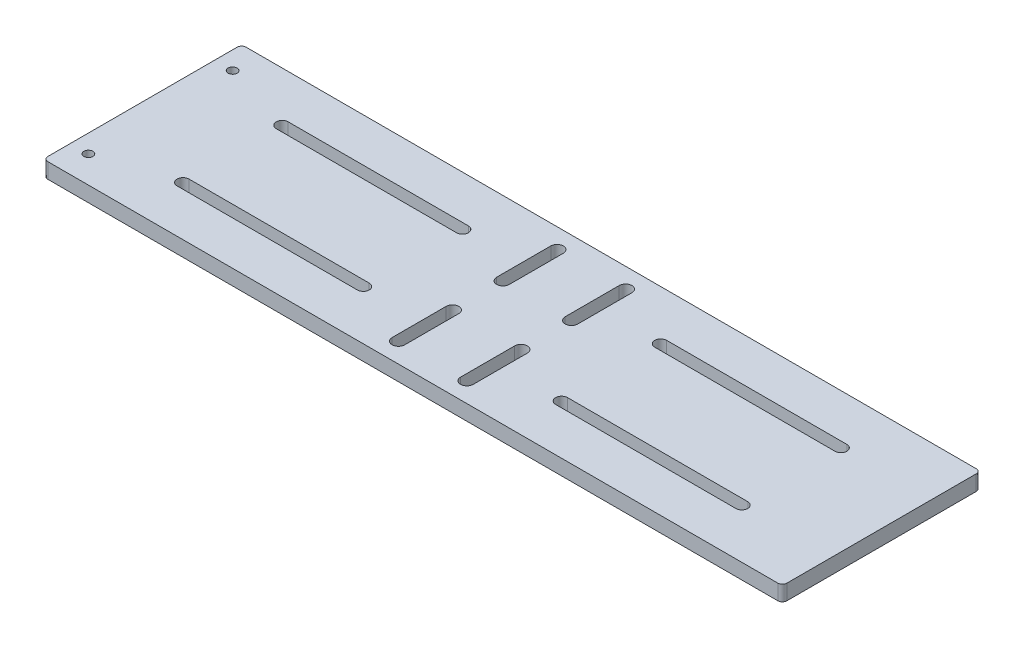
SolidWorks part; units mm, degrees
ref_plane "Front Plane" through (0, 0, 0) normal (0, 0, 1) x (1, 0, 0)
ref_plane "Top Plane" through (0, 0, 0) normal (0, 1, 0) x (1, 0, 0)
ref_plane "Right Plane" through (0, 0, 0) normal (1, 0, 0) x (0, 0, -1)
sketch "Sketch1" plane through (0, 0, 0) normal (0, 1, 0) x (1, 0, 0)
  line L1 (-19, 34) -> (19, 34) construction
  line L2 (-19, 34) -> (-19, -34) construction
  line L3 (-19, -34) -> (19, -34) construction
  line L4 (19, 34) -> (19, -34) construction
  line L5 (0, -34) -> (0, 34) construction
  line L6 (-19, 0) -> (19, 0) construction
  line L7 (-200, 50) -> (200, 50) construction
  line L8 (-200, 50) -> (-200, -50) construction
  line L9 (-200, -50) -> (200, -50) construction
  line L10 (200, 50) -> (200, -50) construction
  line L11 (0, -50) -> (0, 50) construction
  line L12 (-200, 0) -> (200, 0) construction
  line L13 (-205, 55) -> (205, 55)
  line L14 (-205, 55) -> (-205, -55)
  line L15 (-205, -55) -> (205, -55)
  line L16 (205, 55) -> (205, -55)
  line L17 (0, -55) -> (0, 55) construction
  line L18 (-205, 0) -> (205, 0) construction
  point P0 (0, 0)
  point P4 (0, 0)
  point P8 (0, 0)
  point P14 (-190, 40)
  point P16 (-190, -40)
  dimension "D2" = 68
  dimension "D3" = 400
  dimension "D4" = 100
  dimension "D5" = 5
  dimension "D6" = 5
  dimension "D10" = 10
  dimension "D11" = 10
  dimension "D12" = 10
  dimension "D13" = 38
extrude "Boss-Extrude1" add sketch "Sketch1" along normal blind 8.5
sketch "Sketch2" plane through (0, 8.5, 0) normal (0, 1, 0) x (1, 0, 0)
  line L0 (-205, 55) -> (-205, -55) construction
  line L1 (205, 55) -> (-205, 55) construction
  line L2 (-205, -55) -> (205, -55) construction
  point P0 (-195, -40)
  point P2 (-195, 40)
  dimension "D1" = 10
  dimension "D3" = 10
  dimension "D2" = 15
  dimension "D4" = 15
sketch "Sketch3" plane through (0, 8.5, 0) normal (0, 1, 0) x (1, 0, 0)
  point P8 (19, 34)
  point P10 (19, -34)
  point P12 (-19, -34)
  point P14 (-19, 34)
hole_wizard "M4 Clearance Hole1" positions "Sketch2" profile "Sketch4" hole size "M4" standard "ISO" end condition through all
sketch "Sketch4" plane through (-195, 8.5, 40) normal (1, 0, 0) x (0, 0, 1)
  line L0 (0, 0) -> (0, 8.5)
  line L1 (0, 8.5) -> (2.5, 8.5)
  line L2 (2.5, 8.5) -> (2.5, 0)
  line L5 (2.5, 0) -> (0, 0)
  line L11 (0, -6.35) -> (0, 107.95) construction
  dimension "Thru Hole Dia." = 5
  dimension "Thru Hole Depth" = 8.5
hole_wizard "M6 Clearance Hole1" positions "Sketch3" profile "Sketch5" hole size "M6" standard "ISO" end condition through all
sketch "Sketch5" plane through (19, 8.5, -34) normal (1, 0, 0) x (0, 0, 1)
  line L0 (0, 0) -> (0, 8.5)
  line L1 (0, 8.5) -> (3.5, 8.5)
  line L2 (3.5, 8.5) -> (3.5, 0)
  line L5 (3.5, 0) -> (0, 0)
  line L11 (0, -6.35) -> (0, 107.95) construction
  dimension "Thru Hole Dia." = 7
  dimension "Thru Hole Depth" = 8.5
fillet "Fillet1" radius 2.5 4 edges at (205, 4.25, -55) (205, 4.25, 55) (-205, 4.25, 55) (-205, 4.25, -55)
sketch "Sketch6" plane through (0, 8.5, 0) normal (0, 1, 0) x (1, 0, 0)
  line L0 (-22.5, 34) -> (-22.5, 14)
  line L1 (-15.5, 34) -> (-15.5, 14)
  line L2 (-19, 34) -> (19, 34) construction
  line L3 (-19, -34) -> (19, -34) construction
  line L4 (22.5, 34) -> (22.5, 14)
  line L5 (15.5, 34) -> (15.5, 14)
  line L6 (-22.5, 34) -> (-22.5, 44)
  line L7 (-15.5, 34) -> (-15.5, 44)
  line L8 (15.5, 34) -> (15.5, 44)
  line L9 (22.5, 34) -> (22.5, 44)
  line L10 (-22.5, -44) -> (-22.5, -34)
  line L11 (-15.5, -44) -> (-15.5, -34)
  line L12 (15.5, -44) -> (15.5, -34)
  line L13 (22.5, -44) -> (22.5, -34)
  line L14 (-22.5, 14) -> (-22.5, -14) construction
  line L15 (-22.5, -14) -> (-22.5, -34)
  line L16 (-15.5, 14) -> (-15.5, -14) construction
  line L17 (-15.5, -14) -> (-15.5, -34)
  line L18 (15.5, 14) -> (15.5, -14) construction
  line L19 (15.5, -14) -> (15.5, -34)
  line L20 (22.5, 14) -> (22.5, -14) construction
  line L21 (22.5, -14) -> (22.5, -34)
  circle A0 centre (-19, 34) radius 3.5 construction
  circle A1 centre (-19, -34) radius 3.5 construction
  circle A2 centre (19, 34) radius 3.5 construction
  circle A3 centre (19, -34) radius 3.5 construction
  arc A4 (-15.5, 34) -> (-22.5, 34) centre (-19, 34) ccw construction
  arc A5 (22.5, 34) -> (15.5, 34) centre (19, 34) ccw construction
  arc A6 (-22.5, -34) -> (-15.5, -34) centre (-19, -34) ccw construction
  arc A7 (15.5, -34) -> (22.5, -34) centre (19, -34) ccw construction
  arc A8 (-22.5, 34) -> (-15.5, 34) centre (-19, 34) ccw construction
  arc A9 (-15.5, -34) -> (-22.5, -34) centre (-19, -34) ccw construction
  arc A10 (22.5, -34) -> (15.5, -34) centre (19, -34) ccw construction
  arc A11 (15.5, 34) -> (22.5, 34) centre (19, 34) ccw construction
  arc A12 (-15.5, 44) -> (-22.5, 44) centre (-19, 44) ccw
  arc A13 (22.5, 44) -> (15.5, 44) centre (19, 44) ccw
  arc A14 (-22.5, -44) -> (-15.5, -44) centre (-19, -44) ccw
  arc A15 (15.5, -44) -> (22.5, -44) centre (19, -44) ccw
  arc A16 (22.5, -44) -> (15.5, -44) centre (19, -44) ccw construction
  arc A17 (-15.5, -44) -> (-22.5, -44) centre (-19, -44) ccw construction
  arc A18 (-22.5, 44) -> (-15.5, 44) centre (-19, 44) ccw construction
  arc A19 (15.5, 44) -> (22.5, 44) centre (19, 44) ccw construction
  arc A20 (-15.5, -14) -> (-22.5, -14) centre (-19, -14) ccw
  arc A21 (-22.5, 14) -> (-15.5, 14) centre (-19, 14) ccw
  arc A22 (15.5, 14) -> (22.5, 14) centre (19, 14) ccw
  arc A23 (22.5, -14) -> (15.5, -14) centre (19, -14) ccw
  arc A24 (-15.5, 14) -> (-22.5, 14) centre (-19, 14) ccw construction
  arc A25 (22.5, 14) -> (15.5, 14) centre (19, 14) ccw construction
  arc A26 (15.5, -14) -> (22.5, -14) centre (19, -14) ccw construction
  arc A27 (-22.5, -14) -> (-15.5, -14) centre (-19, -14) ccw construction
  dimension "D6" = 7
  dimension "D8" = 7
  dimension "D11" = 7
  dimension "D12" = 7
  dimension "D1" = 10
  dimension "D2" = 10
  dimension "D3" = 10
  dimension "D4" = 10
  dimension "D5" = 20
  dimension "D7" = 20
  dimension "D9" = 20
  dimension "D10" = 20
extrude "Cut-Extrude1" cut sketch "Sketch6" against normal up to surface (8.5 mm away) up to face at (19, 0, -30.5)
sketch "Sketch7" plane through (0, 8.5, 0) normal (0, 1, 0) x (1, 0, 0)
  line L0 (-205, 0) -> (205, 0) construction
  line L1 (-205, 52.5) -> (-205, -52.5) construction
  line L2 (205, -52.5) -> (205, 52.5) construction
  line L3 (-205, 27.5) -> (-158.3, 27.5) construction
  line L4 (-205, -27.5) -> (-158.3, -27.5) construction
  line L5 (202.5, 55) -> (-202.5, 55) construction
  line L6 (-155, 30.8) -> (-55, 30.8)
  line L7 (-155, 24.2) -> (-55, 24.2)
  line L8 (-155, -24.2) -> (-55, -24.2)
  line L9 (-55, -30.8) -> (-155, -30.8)
  line L10 (-158.3, -27.5) -> (-151.7, -27.5) construction
  line L11 (-151.7, -27.5) -> (-58.3, -27.5) construction
  line L12 (-58.3, -27.5) -> (-51.7, -27.5) construction
  line L13 (-51.7, -27.5) -> (51.7, -27.5) construction
  line L14 (-158.3, 27.5) -> (-151.7, 27.5) construction
  line L15 (-151.7, 27.5) -> (-58.3, 27.5) construction
  line L16 (-58.3, 27.5) -> (-51.7, 27.5) construction
  line L17 (-51.7, 27.5) -> (51.7, 27.5) construction
  line L18 (55, -24.2) -> (155, -24.2)
  line L19 (155, -30.8) -> (55, -30.8)
  line L20 (155, 30.8) -> (55, 30.8)
  line L21 (55, 24.2) -> (155, 24.2)
  line L22 (51.7, 27.5) -> (58.3, 27.5) construction
  line L23 (58.3, 27.5) -> (151.7, 27.5) construction
  line L24 (151.7, 27.5) -> (158.3, 27.5) construction
  line L25 (158.3, 27.5) -> (205, 27.5) construction
  line L26 (51.7, -27.5) -> (58.3, -27.5) construction
  line L27 (58.3, -27.5) -> (151.7, -27.5) construction
  line L28 (151.7, -27.5) -> (158.3, -27.5) construction
  line L29 (158.3, -27.5) -> (205, -27.5) construction
  arc A0 (-155, 30.8) -> (-155, 24.2) centre (-155, 27.5) ccw
  arc A1 (-55, 24.2) -> (-55, 30.8) centre (-55, 27.5) ccw
  arc A2 (-155, -24.2) -> (-155, -30.8) centre (-155, -27.5) ccw
  arc A3 (-55, -30.8) -> (-55, -24.2) centre (-55, -27.5) ccw
  arc A4 (-151.7, -27.5) -> (-155, -24.2) centre (-155, -27.5) ccw construction
  arc A5 (-155, -30.8) -> (-151.7, -27.5) centre (-155, -27.5) ccw construction
  arc A6 (-55, -24.2) -> (-58.3, -27.5) centre (-55, -27.5) ccw construction
  arc A7 (-58.3, -27.5) -> (-55, -30.8) centre (-55, -27.5) ccw construction
  arc A8 (-151.7, 27.5) -> (-155, 30.8) centre (-155, 27.5) ccw construction
  arc A9 (-155, 24.2) -> (-151.7, 27.5) centre (-155, 27.5) ccw construction
  arc A10 (-55, 30.8) -> (-58.3, 27.5) centre (-55, 27.5) ccw construction
  arc A11 (-58.3, 27.5) -> (-55, 24.2) centre (-55, 27.5) ccw construction
  arc A12 (55, 30.8) -> (55, 24.2) centre (55, 27.5) ccw
  arc A13 (155, 24.2) -> (155, 30.8) centre (155, 27.5) ccw
  arc A14 (55, -24.2) -> (55, -30.8) centre (55, -27.5) ccw
  arc A15 (155, -30.8) -> (155, -24.2) centre (155, -27.5) ccw
  arc A16 (55, 24.2) -> (58.3, 27.5) centre (55, 27.5) ccw construction
  arc A17 (58.3, 27.5) -> (55, 30.8) centre (55, 27.5) ccw construction
  arc A18 (151.7, 27.5) -> (155, 24.2) centre (155, 27.5) ccw construction
  arc A19 (155, 30.8) -> (151.7, 27.5) centre (155, 27.5) ccw construction
  arc A20 (58.3, -27.5) -> (55, -24.2) centre (55, -27.5) ccw construction
  arc A21 (55, -30.8) -> (58.3, -27.5) centre (55, -27.5) ccw construction
  arc A22 (155, -24.2) -> (151.7, -27.5) centre (155, -27.5) ccw construction
  arc A23 (151.7, -27.5) -> (155, -30.8) centre (155, -27.5) ccw construction
  dimension "D4" = 6.6
  dimension "D9" = 6.6
  dimension "D1" = 27.5
  dimension "D2" = 55
  dimension "D3" = 27.5
  dimension "D5" = 50
  dimension "D6" = 50
  dimension "D7" = 100
  dimension "D8" = 100
  dimension "D10" = 50
  dimension "D11" = 50
  dimension "D12" = 100
  dimension "D13" = 100
extrude "Cut-Extrude2" cut sketch "Sketch7" against normal up to surface (8.5 mm away) up to face at (19, 0, -29)
equation "\"D6@Sketch7\"=\"D5@Sketch7\""
equation "\"D8@Sketch7\"=\"D7@Sketch7\""
equation "\"D9@Sketch7\"=\"D4@Sketch7\""
equation "\"D13@Sketch7\"=\"D7@Sketch7\""
equation "\"D12@Sketch7\"=\"D7@Sketch7\""
equation "\"D11@Sketch7\"=\"D10@Sketch7\""
equation "\"D7@Sketch6\"=\"D5@Sketch6\""
equation "\"D4@Sketch6\"=\"D3@Sketch6\""
equation "\"D8@Sketch6\"=\"D6@Sketch6\""
equation "\"D11@Sketch6\"=\"D6@Sketch6\""
equation "\"D12@Sketch6\"=\"D6@Sketch6\""
equation "\"D2@Sketch6\"=\"D3@Sketch6\""
equation "\"D9@Sketch6\"=\"D5@Sketch6\""
equation "\"D10@Sketch6\"=\"D5@Sketch6\""
equation "\"D4@Sketch2\"=\"D2@Sketch2\""
equation "\"D3@Sketch2\"=\"D1@Sketch2\""
